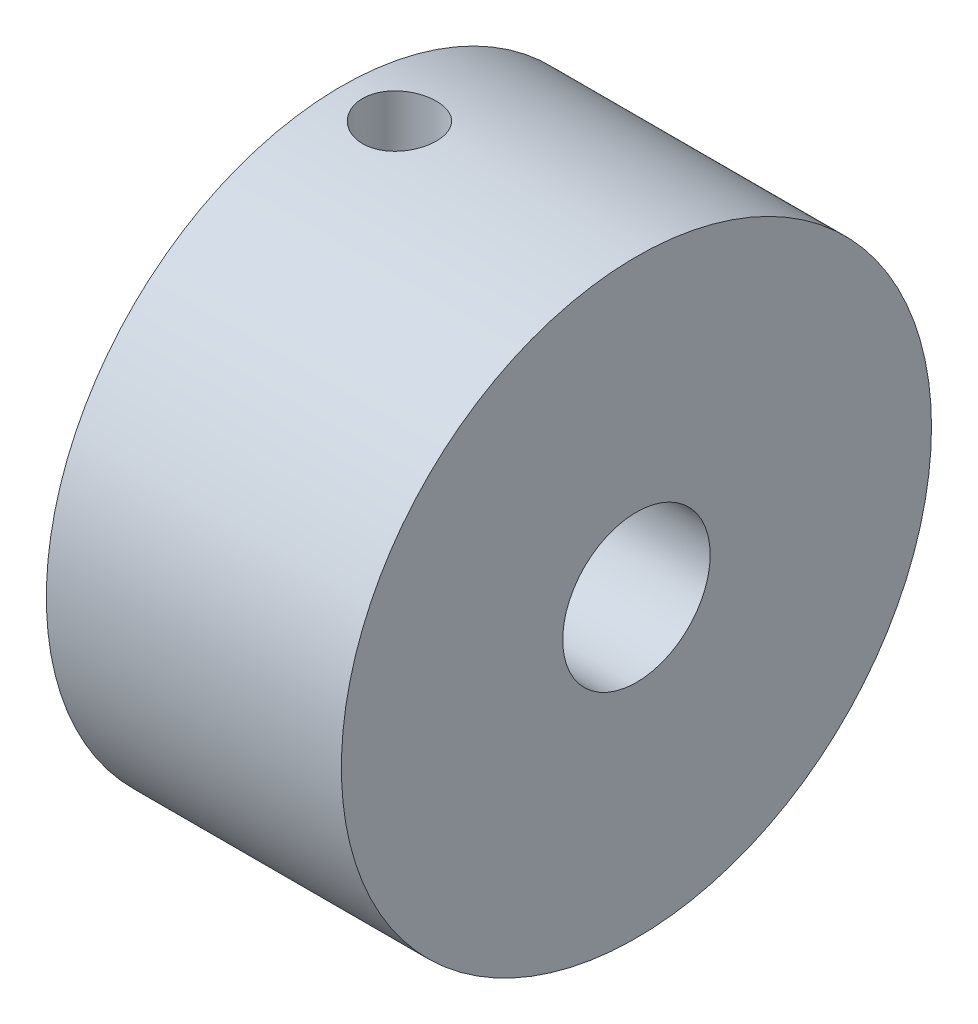
SolidWorks part; units mm, degrees
ref_plane "Front Plane" through (0, 0, 0) normal (0, 0, 1) x (1, 0, 0)
ref_plane "Top Plane" through (0, 0, 0) normal (0, 1, 0) x (1, 0, 0)
ref_plane "Right Plane" through (0, 0, 0) normal (1, 0, 0) x (0, 0, -1)
sketch "Sketch1" plane through (0, 0, 0) normal (1, 0, 0) x (0, 0, -1)
  circle A0 centre (0, 0) radius 12.7
  dimension "D1" = 25.4
extrude "Boss-Extrude1" add sketch "Sketch1" along normal blind 12.7
sketch "Sketch2" plane through (0, 0, 0) normal (-1, 0, 0) x (0, 0, 1)
  circle A0 centre (0, 0) radius 3.5
  dimension "D1" = 7
extrude "Cut-Extrude1" cut sketch "Sketch2" against normal blind 5
sketch "Sketch3" plane through (12.7, 0, 0) normal (1, 0, 0) x (0, 0, -1)
  point P0 (0, 0)
hole_wizard "1/4 (0.25) Diameter Hole1" positions "Sketch5" profile "Sketch4" hole size "1/4" standard "ANSI Inch"
sketch "Sketch5" plane through (12.7, 0, 0) normal (1, 0, 0) x (0, 0, -1)
  point P0 (0, 0)
sketch "Sketch4" plane through (12.7, 0, 0) normal (0, 1, 0) x (0, 0, -1)
  line L0 (0, 0) -> (0, 12.0677)
  line L1 (0, 12.0677) -> (3.175, 10.16)
  line L2 (3.175, 10.16) -> (3.175, 0)
  line L5 (3.175, 0) -> (0, 0)
  line L10 (0, 12.0677) -> (-3.175, 10.16) construction
  line L11 (0, -6.35) -> (0, 107.95) construction
  dimension "Hole Dia." = 6.35
  dimension "Hole Depth" = 10.16
  dimension "Drill Angle" = 118
sketch "Sketch6" plane through (0, 0, 0) normal (0, 1, 0) x (1, 0, 0)
  point P0 (2.5, 0)
  dimension "D1" = 2.5
hole_wizard "1/8 (0.125) Diameter Hole1" positions "Sketch8" profile "Sketch7" hole size "1/8" standard "ANSI Inch"
sketch "Sketch8" plane through (0, 0, 0) normal (0, 1, 0) x (1, 0, 0)
  point P0 (2.5, 0)
sketch "Sketch7" plane through (2.5, 0, 0) normal (1, 0, 0) x (0, 0, -1)
  line L0 (0, 0) -> (0, 16.1939)
  line L1 (0, 16.1939) -> (1.5875, 15.24)
  line L2 (1.5875, 15.24) -> (1.5875, 0)
  line L5 (1.5875, 0) -> (0, 0)
  line L10 (0, 16.1939) -> (-1.5875, 15.24) construction
  line L11 (0, -6.35) -> (0, 107.95) construction
  dimension "Hole Dia." = 3.175
  dimension "Hole Depth" = 15.24
  dimension "Drill Angle" = 118
